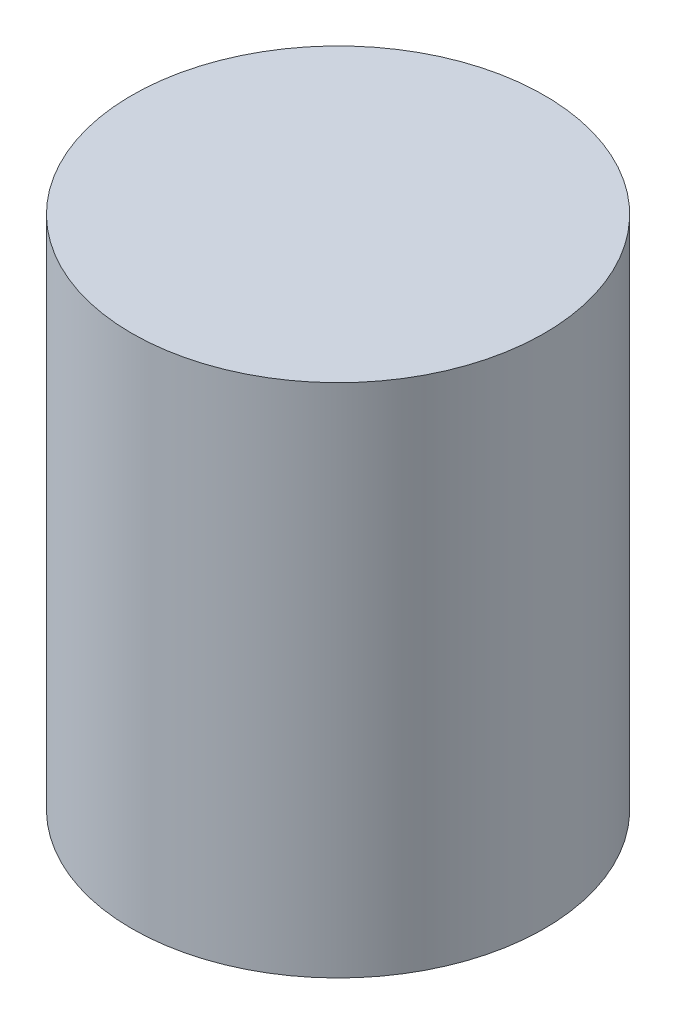
SolidWorks part; units mm, degrees
material "Hexcel AS4C (3000 Filaments)"
ref_plane "Płaszczyzna przednia" through (0, 0, 0) normal (0, 0, 1) x (1, 0, 0)
ref_plane "Płaszczyzna górna" through (0, 0, 0) normal (0, 1, 0) x (1, 0, 0)
ref_plane "Płaszczyzna prawa" through (0, 0, 0) normal (1, 0, 0) x (0, 0, -1)
sketch "Sketch1" plane through (0, 0, 0) normal (0, 1, 0) x (1, 0, 0)
  circle A0 centre (0, 0) radius 85 construction
  circle A1 centre (0, 0) radius 60
  dimension "D1" = 170
  dimension "D2" = 120
extrude "Boss-Extrude1" add sketch "Sketch1" along normal blind 150
